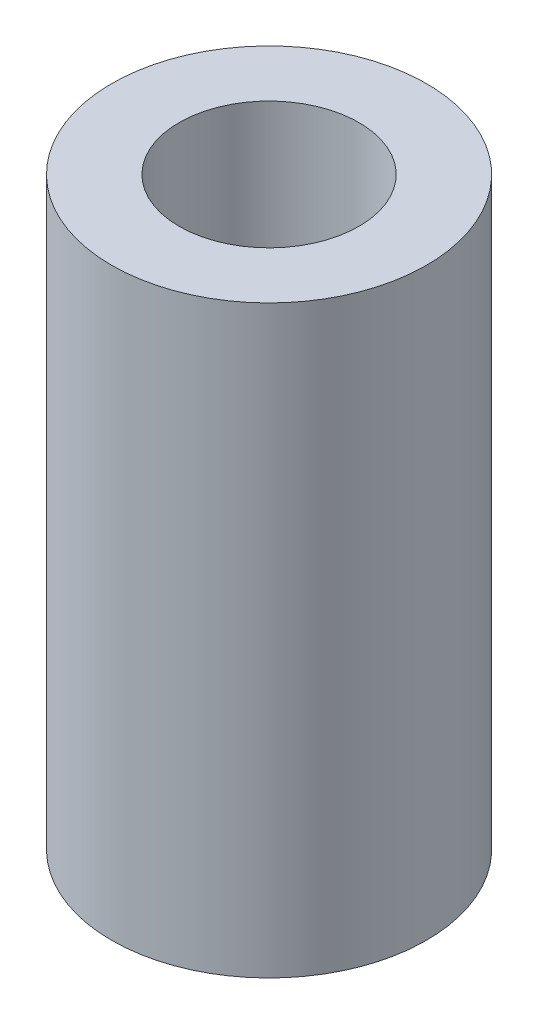
SolidWorks part; units mm, degrees
ref_plane "Plan de face" through (0, 0, 0) normal (0, 0, 1) x (1, 0, 0)
ref_plane "Plan de dessus" through (0, 0, 0) normal (0, 1, 0) x (1, 0, 0)
ref_plane "Plan de droite" through (0, 0, 0) normal (1, 0, 0) x (0, 0, -1)
sketch "Esquisse1" plane through (0, 0, 0) normal (0, 1, 0) x (1, 0, 0)
  circle A0 centre (0, 0) radius 20
  circle A1 centre (0, 0) radius 35
  dimension "D1" = 40
  dimension "D2" = 70
extrude "Boss.-Extru.1" add sketch "Esquisse1" along normal blind 130
sketch "Esquisse2" plane through (0, 0, 0) normal (0, 0, 1) x (1, 0, 0)
  line L0 (0, 130) -> (0, 90) construction
  line L1 (35, 130) -> (-35, 130) construction
  line L2 (0, 0) -> (0, 40) construction
  line L3 (-35, 0) -> (35, 0) construction
  circle A2 centre (0, 90) radius 8.75
  circle A3 centre (0, 40) radius 8.75
  point P8 (0, 90.8298)
  point P12 (0, 40.4429)
  dimension "D1" = 17.5
  dimension "D2" = 17.5
  dimension "D3" = 40
  dimension "D4" = 40
extrude "Enlèv. mat.-Extru.1" cut sketch "Esquisse2" against normal blind 100 from offset 25 offset against normal yes
ref_plane "Plan1" through (-35, 0, 0) normal (1, 0, 0) x (0, 0, -1)
sketch "Esquisse3" plane through (-35, 0, 0) normal (1, 0, 0) x (0, 0, -1)
  line L0 (0, 130) -> (0, 100) construction
  line L2 (35, 130) -> (-35, 130) construction
  line L3 (0, 0) -> (0, 30) construction
  circle A0 centre (0, 100) radius 7.5
  circle A1 centre (0, 30) radius 7.5
  point P5 (0, 40.4833)
  dimension "D1" = 15
  dimension "D2" = 15
  dimension "D3" = 30
  dimension "D4" = 30
extrude "Enlèv. mat.-Extru.2" cut sketch "Esquisse3" along normal blind 10
